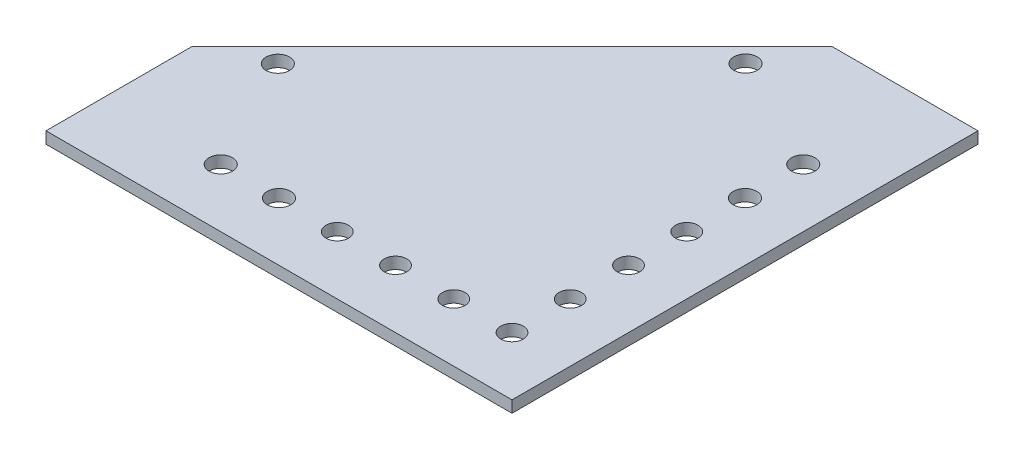
SolidWorks part; units mm, degrees
ref_plane "Front Plane" through (0, 0, 0) normal (0, 0, 1) x (1, 0, 0)
ref_plane "Top Plane" through (0, 0, 0) normal (0, 1, 0) x (1, 0, 0)
ref_plane "Right Plane" through (0, 0, 0) normal (1, 0, 0) x (0, 0, -1)
sketch "Sketch1" plane through (0, 0, 0) normal (0, 1, 0) x (1, 0, 0)
  line L0 (53.8359, 81.9942) -> (53.8359, -36.0255)
  line L1 (53.8359, -36.0255) -> (-64.1839, -36.0255)
  line L2 (-68.674, -25.1854) -> (42.9957, 86.4844)
  arc A0 (53.8359, 81.9942) -> (42.9957, 86.4844) centre (47.4859, 81.9942) ccw
  arc A1 (-64.1839, -36.0255) -> (-68.674, -25.1854) centre (-64.1839, -29.6755) cw
  point P5 (53.8359, 97.3245)
  point P8 (-79.5141, -36.0255)
  dimension "D3" = 6.35
  dimension "D1" = 133.35
  dimension "D2" = 133.35
extrude "Boss-Extrude1" add sketch "Sketch1" along normal mid plane 2.54
hole_wizard "#10 (0.1935) Diameter Hole1" positions "Sketch4" profile "Sketch5" hole size "#10" standard "ANSI Inch" end condition through all
sketch "Sketch4" plane through (0, 1.27, 0) normal (0, 1, 0) x (1, 0, 0)
  line L0 (53.8359, -36.0255) -> (53.8359, 81.9942) construction
  line L1 (-64.1839, -36.0255) -> (53.8359, -36.0255) construction
  point P0 (41.1359, -23.3255)
  point P2 (28.4359, -23.3255)
  point P4 (15.7359, -23.3255)
  point P6 (3.0359, -23.3255)
  point P8 (41.1359, -10.6255)
  point P10 (41.1359, 2.0745)
  point P12 (41.1359, 14.7745)
  dimension "D1" = 12.7
  dimension "D2" = 12.7
  dimension "D3" = 12.7
  dimension "D4" = 12.7
  dimension "D5" = 12.7
  dimension "D6" = 12.7
  dimension "D7" = 12.7
  dimension "D8" = 12.7
  dimension "D9" = 12.7
  dimension "D10" = 12.7
  dimension "D11" = 12.7
  dimension "D12" = 12.7
  dimension "D13" = 12.7
  dimension "D14" = 12.7
sketch "Sketch5" plane through (41.1359, 1.27, 23.3255) normal (1, 0, 0) x (0, 0, 1)
  line L0 (0, 0) -> (0, 2.54)
  line L1 (0, 2.54) -> (2.4574, 2.54)
  line L2 (2.4574, 2.54) -> (2.4574, 0)
  line L5 (2.4574, 0) -> (0, 0)
  line L11 (0, -6.35) -> (0, 107.95) construction
  dimension "Thru Hole Dia." = 4.9149
  dimension "Thru Hole Depth" = 2.54
hole_wizard "#10 Clearance Hole3" positions "Sketch6" profile "Sketch7" hole size "#10" standard "ANSI Inch" end condition through all
sketch "Sketch6" plane through (0, 1.27, 0) normal (0, 1, 0) x (1, 0, 0)
  line L0 (53.8359, -36.0255) -> (53.8359, 81.9942) construction
  line L1 (-64.1839, -36.0255) -> (53.8359, -36.0255) construction
  point P0 (-9.6641, -23.3255)
  point P2 (-22.3641, -23.3255)
  point P4 (41.1359, 27.4745)
  point P6 (41.1359, 40.1745)
  point P22 (15.7958, 52.9298)
  point P24 (-35.1539, 1.9026)
  point P27 (13.4826, 49.7666)
  point P28 (-43.1797, -9.0301)
  point P29 (17.0263, 52.9746)
  point P30 (16.421, 52.9507)
  point P31 (15.7958, 52.9298)
  point P32 (-34.5416, -0.8091)
  point P33 (-35.1539, 1.9026)
  point P34 (0, 0)
  point P35 (0, 0)
  dimension "D2" = 12.7
  dimension "D3" = 12.7
  dimension "D4" = 12.7
  dimension "D5" = 12.7
  dimension "D7" = 12.7
  dimension "D8" = 12.7
sketch "Sketch7" plane through (-9.6641, 1.27, 23.3255) normal (1, 0, 0) x (0, 0, 1)
  line L0 (0, 0) -> (0, 2.54)
  line L1 (0, 2.54) -> (2.5527, 2.54)
  line L2 (2.5527, 2.54) -> (2.5527, 0)
  line L5 (2.5527, 0) -> (0, 0)
  line L11 (0, -6.35) -> (0, 107.95) construction
  dimension "Thru Hole Dia." = 5.1054
  dimension "Thru Hole Depth" = 2.54
sketch "Sketch8" plane through (0, 1.27, 0) normal (0, 1, 0) x (1, 0, 0)
  line L1 (53.8359, -36.0255) -> (-47.7641, -36.0255)
  line L2 (53.8359, -36.0255) -> (53.8359, 65.5745)
  line L3 (53.8359, 65.5745) -> (-47.7641, 65.5745)
  line L4 (-47.7641, -36.0255) -> (-47.7641, 65.5745)
  line L5 (-77.0871, 91.7396) -> (105.1859, 91.7396)
  line L6 (-77.0871, 91.7396) -> (-77.0871, -51.0197)
  line L7 (-77.0871, -51.0197) -> (105.1859, -51.0197)
  line L8 (105.1859, 91.7396) -> (105.1859, -51.0197)
  dimension "D1" = 101.6
  dimension "D2" = 101.6
extrude "Cut-Extrude1" cut sketch "Sketch8" against normal through all
